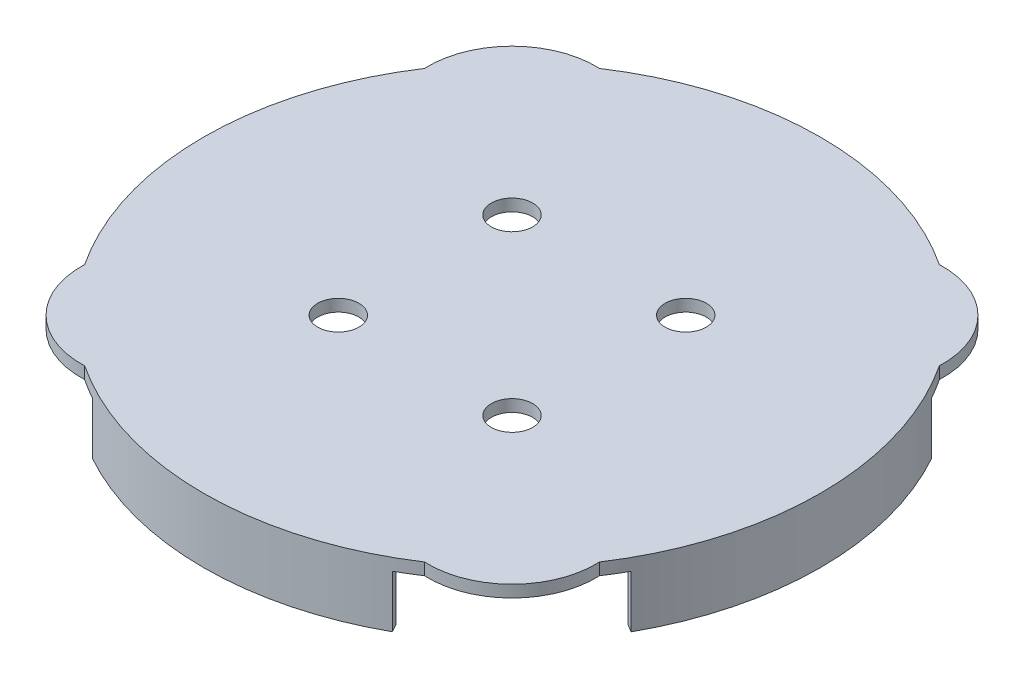
SolidWorks part; units mm, degrees
ref_plane "Front Plane" through (0, 0, 0) normal (0, 0, 1) x (1, 0, 0)
ref_plane "Top Plane" through (0, 0, 0) normal (0, 1, 0) x (1, 0, 0)
ref_plane "Right Plane" through (0, 0, 0) normal (1, 0, 0) x (0, 0, -1)
sketch "Sketch1" plane through (0, 0, 0) normal (0, 1, 0) x (1, 0, 0)
  line L4 (0, 29) -> (29, 0) construction
  circle A1 centre (0, 0) radius 14 construction
  circle A2 centre (29, 0) radius 14 construction
  circle A3 centre (-29, 0) radius 14 construction
  arc A4 (28.3636, -42.9855) -> (42.9855, -28.3636) centre (29, -29) ccw
  circle A5 centre (0, -29) radius 14 construction
  arc A6 (-42.9855, -28.3636) -> (-28.3636, -42.9855) centre (-29, -29) ccw
  arc A7 (42.9855, 28.3636) -> (28.3636, 42.9855) centre (29, 29) ccw
  circle A8 centre (0, 29) radius 14 construction
  arc A9 (-28.3636, 42.9855) -> (-42.9855, 28.3636) centre (-29, 29) ccw
  arc A13 (-28.3636, -42.9855) -> (28.3636, -42.9855) centre (0, 0) ccw
  arc A14 (42.9855, -28.3636) -> (42.9855, 28.3636) centre (0, 0) ccw
  arc A15 (28.3636, 42.9855) -> (-28.3636, 42.9855) centre (0, 0) ccw
  arc A16 (-42.9855, 28.3636) -> (-42.9855, -28.3636) centre (0, 0) ccw
  circle A18 centre (14.5, 14.5) radius 3.45
  circle A19 centre (-14.5, 14.5) radius 3.45
  circle A20 centre (-14.5, -14.5) radius 3.45
  circle A21 centre (14.5, -14.5) radius 3.45
  dimension "D1" = 6.9
  dimension "D2" = 28
  dimension "D5" = 29
  dimension "D8" = 29
  dimension "D11" = 2
  dimension "D9" = 103
  dimension "D3" = 29
  dimension "D4" = 29
  dimension "D6" = 3
  dimension "D7" = 2
  dimension "D10" = 2
extrude "Boss-Extrude1" add sketch "Sketch1" along normal blind 2
sketch "Sketch2" plane through (0, 0, 0) normal (0, -1, 0) x (1, 0, 0)
  line L0 (43.6903, -24.3137) -> (45.001, -25.0431)
  line L1 (44.9728, 25.0938) -> (43.6903, 24.3137)
  arc A0 (43.6903, -24.3137) -> (43.6903, 24.3137) centre (0, 0) ccw
  arc A4 (45.001, -25.0431) -> (44.9728, 25.0938) centre (0, 0) ccw
  dimension "D1" = 50
extrude "Boss-Extrude2" add sketch "Sketch2" along normal blind 8.75
pattern_circular "CirPattern1" count 4 over 360 about axis through (0, 0, 0) along (0, 1, 0) of "Boss-Extrude2"
